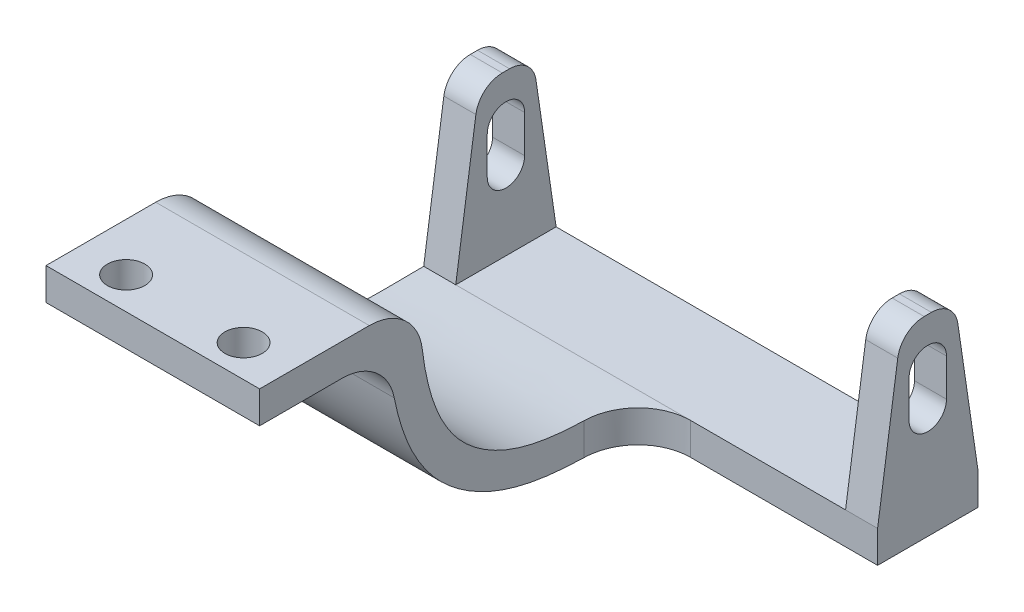
SolidWorks part; units mm, degrees
ref_plane "前视基准面" through (0, 0, 0) normal (0, 0, 1) x (1, 0, 0)
ref_plane "上视基准面" through (0, 0, 0) normal (0, 1, 0) x (1, 0, 0)
ref_plane "右视基准面" through (0, 0, 0) normal (1, 0, 0) x (0, 0, -1)
sketch "草图2" plane through (0, 0, 0) normal (0, 1, 0) x (1, 0, 0)
  line L1 (21.25, -4.7) -> (-21.25, -4.7)
  line L2 (21.25, -4.7) -> (21.25, 4.7)
  line L3 (21.25, 4.7) -> (-21.25, 4.7)
  line L4 (-21.25, -4.7) -> (-21.25, 4.7)
  line L5 (21.25, -4.7) -> (-21.25, 4.7) construction
  line L6 (21.25, 4.7) -> (-21.25, -4.7) construction
  point P0 (0, 0)
  dimension "D1" = 42.5
  dimension "D2" = 9.4
extrude "凸台-拉伸1" add sketch "草图2" along normal blind 3
sketch "草图3" plane through (0, 3, 0) normal (0, 1, 0) x (1, 0, 0)
  line L0 (-21.25, -4.7) -> (21.25, -4.7) construction
  line L1 (-21.25, 4.7) -> (-18.25, 4.7)
  line L2 (-21.25, 4.7) -> (-21.25, -4.7)
  line L3 (-21.25, -4.7) -> (-18.25, -4.7)
  line L4 (-18.25, 4.7) -> (-18.25, -4.7)
  line L5 (0, 0) -> (0, 4.7) construction
  line L6 (21.25, 4.7) -> (18.25, 4.7)
  line L7 (21.25, 4.7) -> (21.25, -4.7)
  line L8 (21.25, -4.7) -> (18.25, -4.7)
  line L9 (18.25, 4.7) -> (18.25, -4.7)
  line L10 (21.25, 4.7) -> (-21.25, 4.7) construction
  dimension "D1" = 3
extrude "凸台-拉伸2" add sketch "草图3" along normal blind 15
sketch "草图7" plane through (21.25, 0, 0) normal (1, 0, 0) x (0, 0, -1)
  line L0 (-4.7, 18) -> (4.7, 18) construction
  line L1 (0, 13.75) -> (0, 10.25) construction
  line L2 (1.75, 13.75) -> (1.75, 10.25)
  line L3 (-1.75, 13.75) -> (-1.75, 10.25)
  circle A0 centre (0, 12) radius 1.75 construction
  arc A1 (1.75, 13.75) -> (-1.75, 13.75) centre (0, 13.75) ccw
  arc A2 (-1.75, 10.25) -> (1.75, 10.25) centre (0, 10.25) ccw
  point P5 (0, 18)
  point P7 (0, 12)
  dimension "D1" = 3.5
  dimension "D2" = 6
extrude "切除-拉伸3" cut sketch "草图7" against normal through all
sketch "草图8" plane through (21.25, 0, 0) normal (1, 0, 0) x (0, 0, -1)
  line L0 (-4.7, 3) -> (-2.5, 18)
  line L1 (-4.7, 18) -> (4.7, 18) construction
  line L2 (-2.5, 18) -> (-2.5, 19)
  line L3 (-2.5, 19) -> (2.5, 19)
  line L4 (2.5, 19) -> (2.5, 18)
  line L5 (2.5, 18) -> (4.7, 3)
  line L6 (4.7, 3) -> (5.7, 3)
  line L7 (5.7, 3) -> (5.7, 21)
  line L8 (5.7, 21) -> (-5.7, 21)
  line L9 (-5.7, 21) -> (-5.7, 3)
  line L10 (-5.7, 3) -> (-4.7, 3)
  line L11 (0, 18) -> (0, 11.019) construction
  dimension "D1" = 5
  dimension "D2" = 1
  dimension "D3" = 3
  dimension "D4" = 1
  dimension "D5" = 1
extrude "切除-拉伸4" cut sketch "草图8" against normal through all
fillet "圆角2" radius 2.5 4 edges at (-19.75, 18, -2.5) (-19.75, 18, 2.5) (19.75, 18, 2.5) (19.75, 18, -2.5)
sketch "草图11" plane through (-21.25, 0, 0) normal (-1, 0, 0) x (0, 0, 1)
  line L0 (4.7, 3) -> (25.0629, 3) construction
  line L1 (25.0629, 3) -> (25.0629, 20.7439) construction
  line L2 (4.7, 0) -> (4.7, 3)
  line L3 (4.7, 3) -> (2.8135, 15.8628) construction
  line L4 (25.0629, 20.7439) -> (28.0629, 20.7439)
  spline S0 degree 3 poles (4.7, 3) (6.9625, 3) (10.1418, 2.8629) (16.3375, 3.5282) (24.2316, 8.2979) (25.0629, 16.3796) (25.0629, 20.7439) knots 0 0 0 0 0.173642 0.358242 0.556224 1 1 1 1
  spline S1 degree 1 poles (4.7, 0) (28.0629, 20.7439) knots 0 0 1 1 construction
  spline S2 degree 3 poles (4.7, 0) (5.077, 0) (5.8552, -0.0042) (7.2176, -0.0205) (8.8107, -0.0393) (10.7673, 0.0007) (12.948, 0.1709) (15.2493, 0.5457) (17.6283, 1.2293) (19.9036, 2.2727) (21.9979, 3.6621) (23.8592, 5.447) (25.7879, 8.2201) (26.9376, 11.2471) (27.5958, 14.2982) (27.8925, 16.5541) (28.0144, 18.3639) (28.0569, 19.7544) (28.0629, 20.4109) (28.0629, 20.7439) knots 0 0 0 0 0.03125 0.0625 0.125 0.1875 0.25 0.3125 0.375 0.4375 0.5 0.5625 0.625 0.75 0.8125 0.875 0.9375 0.96875 1 1 1 1
extrude "凸台-拉伸5" add sketch "草图11" against normal blind 20
sketch "草图12" plane through (0, 20.7439, 0) normal (0, 1, 0) x (1, 0, 0)
  line L0 (-1.25, -28.0629) -> (-1.25, -25.0629) construction
  line L1 (-21.25, -25.0629) -> (-1.25, -25.0629)
  line L2 (-21.25, -25.0629) -> (-21.25, -40.0629)
  line L3 (-21.25, -40.0629) -> (-1.25, -40.0629)
  line L4 (-1.25, -25.0629) -> (-1.25, -40.0629)
  dimension "D1" = 15
extrude "凸台-拉伸6" add sketch "草图12" against normal blind 3
fillet "圆角3" radius 5 2 edges at (-11.25, 17.7439, 27.9676) (-11.25, 20.7439, 25.0629)
sketch "草图13" plane through (0, 17.7439, 0) normal (0, -1, 0) x (1, 0, 0)
  line L0 (-11.25, 40.0629) -> (-11.25, 33.3844) construction
  line L1 (-21.25, 40.0629) -> (-1.25, 40.0629) construction
  circle A0 centre (-5.75, 37.0629) radius 1.75
  circle A1 centre (-16.75, 37.0629) radius 1.75
  dimension "D1" = 3.5
  dimension "D3" = 3
  dimension "D2" = 11
extrude "切除-拉伸5" cut sketch "草图13" against normal through all
fillet "圆角4" radius 5 1 edges
